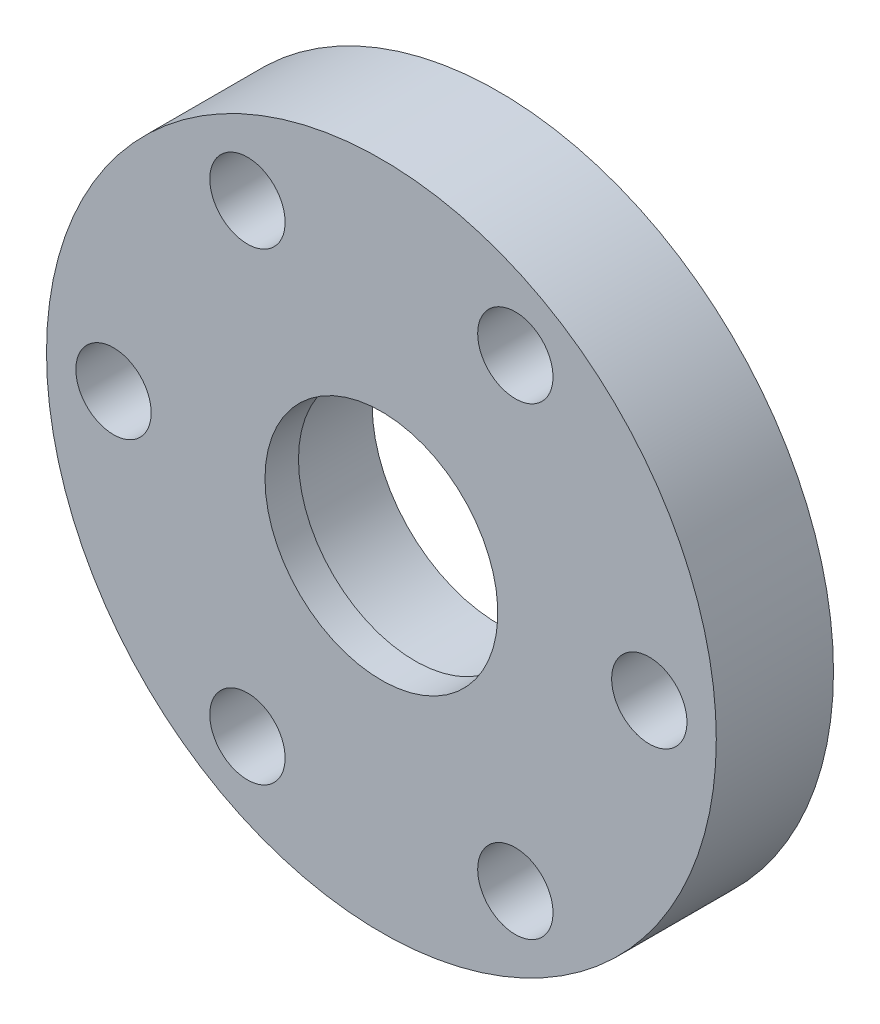
SolidWorks part; units mm, degrees
ref_plane "Front Plane" through (0, 0, 0) normal (0, 0, 1) x (1, 0, 0)
ref_plane "Top Plane" through (0, 0, 0) normal (0, 1, 0) x (1, 0, 0)
ref_plane "Right Plane" through (0, 0, 0) normal (1, 0, 0) x (0, 0, -1)
sketch "Sketch1" plane through (0, 0, -43.4) normal (0, 0, -1) x (-1, 0, 0)
  circle A0 centre (0, 0) radius 20.0025
  circle A1 centre (0, 0) radius 7.55
extrude "Boss-Extrude1" add sketch "Sketch1" along normal blind 7
sketch "Sketch2" plane through (0, 0, -43.4) normal (0, 0, -1) x (-1, 0, 0)
  circle A0 centre (0, 0) radius 6.9526
  circle A1 centre (0, 0) radius 7.55
extrude "Boss-Extrude2" add sketch "Sketch2" along normal blind 2
sketch "Sketch3" plane through (0, 0, -50.4) normal (0, 0, -1) x (-1, 0, 0)
  line L0 (0, 0) -> (16, 0) construction
  circle A0 centre (16, 0) radius 2.25
  circle A1 centre (8, -13.8564) radius 2.25
  circle A2 centre (-8, -13.8564) radius 2.25
  circle A3 centre (-16, 0) radius 2.25
  circle A4 centre (-8, 13.8564) radius 2.25
  circle A5 centre (8, 13.8564) radius 2.25
  point P16 (0, 0)
  dimension "D1" = 6
extrude "Cut-Extrude1" cut sketch "Sketch3" against normal blind 7
